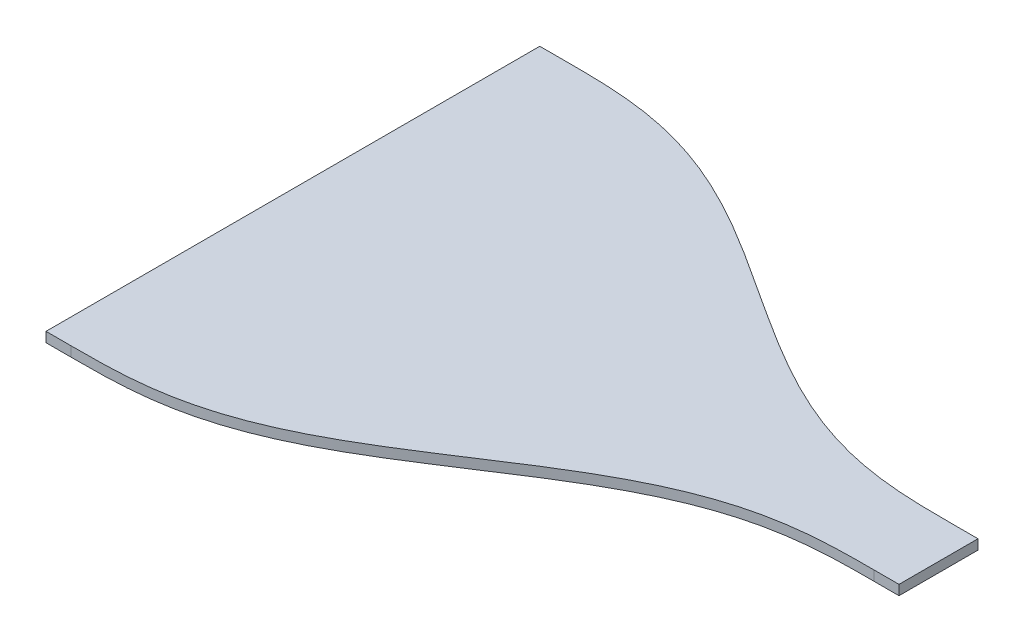
SolidWorks part; units mm, degrees
ref_plane "Front Plane" through (0, 0, 0) normal (0, 0, 1) x (1, 0, 0)
ref_plane "Top Plane" through (0, 0, 0) normal (0, 1, 0) x (1, 0, 0)
ref_plane "Right Plane" through (0, 0, 0) normal (1, 0, 0) x (0, 0, -1)
sketch "Sketch2" plane through (0, 0, 0) normal (0, 1, 0) x (1, 0, 0)
  line L3 (602.96, -40) -> (628.36, -40)
  line L5 (602.96, 40) -> (628.36, 40)
  line L6 (628.36, -40) -> (628.36, 40)
  line L7 (0, -250) -> (-25.4, -250)
  line L9 (0, 250) -> (-25.4, 250)
  line L10 (-25.4, -250) -> (-25.4, 250)
  spline S0 degree 4 poles (-60.296, 252.4276) (-59.6479, 252.3457) (-58.3512, 252.1869) (-55.7553, 251.8889) (-52.5053, 251.5632) (-49.2514, 251.2806) (-45.9942, 251.0374) (-43.3873, 250.865) (-40.1984, 250.6795) (-36.43, 250.4965) (-32.0757, 250.3311) (-27.1465, 250.1957) (-22.8206, 250.1151) (-19.1349, 250.0676) (-16.015, 250.0399) (-13.6544, 250.0237) (-10.2667, 250.0099) (-7.2918, 250.0014) (-1.3526, 249.9994) (1.6906, 250.0007) (8.7963, 249.9978) (12.3138, 249.984) (16.9488, 249.9592) (20.6777, 249.9212) (24.8671, 249.8682) (29.4538, 249.7806) (34.8728, 249.6388) (40.3351, 249.4443) (45.9673, 249.187) (53.1775, 248.7716) (61.9888, 248.109) (72.2406, 247.0857) (83.9178, 245.5398) (95.5332, 243.5951) (107.0739, 241.2402) (118.5221, 238.4733) (132.7008, 234.509) (146.6848, 229.8935) (160.4546, 224.6773) (174.0447, 218.911) (184.8318, 213.9822) (195.4918, 208.7847) (206.0311, 203.3471) (216.4219, 197.7179) (226.675, 191.9256) (239.3776, 184.488) (254.461, 175.2946) (271.8765, 164.277) (291.629, 151.4513) (311.331, 138.5487) (331.0835, 125.723) (350.987, 113.1315) (371.1397, 100.9404) (389.1095, 90.7617) (404.8218, 82.5056) (418.1282, 76.0178) (428.9153, 71.089) (439.795, 66.4727) (450.7673, 62.1931) (461.8688, 58.2603) (473.095, 54.6982) (484.4377, 51.5266) (495.8864, 48.7599) (505.9837, 46.6993) (514.687, 45.1895) (521.9646, 44.0987) (527.8037, 43.3243) (533.6484, 42.6455) (539.514, 42.0586) (545.3692, 41.5597) (551.2611, 41.1438) (558.313, 40.7359) (565.3355, 40.443) (572.0567, 40.2444) (578.9325, 40.1193) (583.9855, 40.0545) (589.9195, 40.018) (594.2835, 40.0022) (601.2169, 39.9993) (604.3716, 40.0006) (610.8787, 39.9983) (615.0042, 39.9853) (620.4039, 39.9539) (625.0734, 39.8964) (630.1528, 39.8043) (635.0101, 39.6689) (640.0581, 39.4787) (645.1061, 39.2211) (650.2649, 38.8825) (655.4615, 38.4475) (659.3679, 38.0439) (661.9588, 37.7362) (663.2561, 37.5724) knots 0 0 0 0 0 0.003383 0.006765 0.01353 0.016913 0.020295 0.023678 0.02706 0.03345 0.039839 0.046228 0.052617 0.055812 0.059006 0.062201 0.065396 0.071785 0.078174 0.085116 0.092059 0.099001 0.102472 0.105943 0.112885 0.119827 0.126769 0.133711 0.141334 0.148956 0.1642 0.179444 0.194688 0.209932 0.225176 0.24042 0.255664 0.286153 0.301397 0.316641 0.3321 0.347559 0.362803 0.378047 0.393291 0.408535 0.439023 0.469512 0.5 0.530488 0.560977 0.591465 0.621953 0.652441 0.6679 0.683359 0.698603 0.713847 0.729091 0.744336 0.75958 0.774824 0.790068 0.805312 0.812934 0.820556 0.828178 0.8358 0.843422 0.851044 0.858666 0.866289 0.880173 0.887115 0.894057 0.900999 0.907941 0.914884 0.921826 0.928215 0.934604 0.940994 0.947383 0.953772 0.960161 0.96655 0.97294 0.979705 0.98647 0.993235 1 1 1 1 1 construction
  spline S1 degree 4 poles (0, 250) (1.131, 250) (3.3588, 250) (8.7963, 249.9978) (12.3138, 249.984) (16.9488, 249.9592) (20.6777, 249.9212) (24.8671, 249.8682) (29.4538, 249.7806) (34.8728, 249.6388) (40.3351, 249.4443) (45.9673, 249.187) (53.1775, 248.7716) (61.9888, 248.109) (72.2406, 247.0857) (83.9178, 245.5398) (95.5332, 243.5951) (107.0739, 241.2402) (118.5221, 238.4733) (132.7008, 234.509) (146.6848, 229.8935) (160.4546, 224.6773) (174.0447, 218.911) (184.8318, 213.9822) (195.4918, 208.7847) (206.0311, 203.3471) (216.4219, 197.7179) (226.675, 191.9256) (239.3776, 184.488) (254.461, 175.2946) (271.8765, 164.277) (291.629, 151.4513) (311.331, 138.5487) (331.0835, 125.723) (350.987, 113.1315) (371.1397, 100.9404) (389.1095, 90.7617) (404.8218, 82.5056) (418.1282, 76.0178) (428.9153, 71.089) (439.795, 66.4727) (450.7673, 62.1931) (461.8688, 58.2603) (473.095, 54.6982) (484.4377, 51.5266) (495.8864, 48.7599) (505.9837, 46.6993) (514.687, 45.1895) (521.9646, 44.0987) (527.8037, 43.3243) (533.6484, 42.6455) (539.514, 42.0586) (545.3692, 41.5597) (551.2611, 41.1438) (558.313, 40.7359) (565.3355, 40.443) (572.0567, 40.2444) (578.9325, 40.1193) (583.9855, 40.0545) (589.9195, 40.018) (594.2835, 40.0022) (599.5892, 40) (601.829, 40) (602.96, 40) knots 0.078174 0.078174 0.078174 0.078174 0.078174 0.085116 0.092059 0.099001 0.102472 0.105943 0.112885 0.119827 0.126769 0.133711 0.141334 0.148956 0.1642 0.179444 0.194688 0.209932 0.225176 0.24042 0.255664 0.286153 0.301397 0.316641 0.3321 0.347559 0.362803 0.378047 0.393291 0.408535 0.439023 0.469512 0.5 0.530488 0.560977 0.591465 0.621953 0.652441 0.6679 0.683359 0.698603 0.713847 0.729091 0.744336 0.75958 0.774824 0.790068 0.805312 0.812934 0.820556 0.828178 0.8358 0.843422 0.851044 0.858666 0.866289 0.880173 0.887115 0.894057 0.900999 0.907941 0.914884 0.921826 0.921826 0.921826 0.921826 0.921826
  spline S2 degree 4 poles (-60.296, -252.4276) (-59.6479, -252.3457) (-58.3512, -252.1869) (-55.7553, -251.8889) (-52.5053, -251.5632) (-49.2514, -251.2806) (-45.9942, -251.0374) (-43.3873, -250.865) (-40.1984, -250.6795) (-36.43, -250.4965) (-32.0757, -250.3311) (-27.1465, -250.1957) (-22.8206, -250.1151) (-19.1349, -250.0676) (-16.015, -250.0399) (-13.6544, -250.0237) (-10.2667, -250.0099) (-7.2918, -250.0014) (-1.3526, -249.9994) (1.6906, -250.0007) (8.7963, -249.9978) (12.3138, -249.984) (16.9488, -249.9592) (20.6777, -249.9212) (24.8671, -249.8682) (29.4538, -249.7806) (34.8728, -249.6388) (40.3351, -249.4443) (45.9673, -249.187) (53.1775, -248.7716) (61.9888, -248.109) (72.2406, -247.0857) (83.9178, -245.5398) (95.5332, -243.5951) (107.0739, -241.2402) (118.5221, -238.4733) (132.7008, -234.509) (146.6848, -229.8935) (160.4546, -224.6773) (174.0447, -218.911) (184.8318, -213.9822) (195.4918, -208.7847) (206.0311, -203.3471) (216.4219, -197.7179) (226.675, -191.9256) (239.3776, -184.488) (254.461, -175.2946) (271.8765, -164.277) (291.629, -151.4513) (311.331, -138.5487) (331.0835, -125.723) (350.987, -113.1315) (371.1397, -100.9404) (389.1095, -90.7617) (404.8218, -82.5056) (418.1282, -76.0178) (428.9153, -71.089) (439.795, -66.4727) (450.7673, -62.1931) (461.8688, -58.2603) (473.095, -54.6982) (484.4377, -51.5266) (495.8864, -48.7599) (505.9837, -46.6993) (514.687, -45.1895) (521.9646, -44.0987) (527.8037, -43.3243) (533.6484, -42.6455) (539.514, -42.0586) (545.3692, -41.5597) (551.2611, -41.1438) (558.313, -40.7359) (565.3355, -40.443) (572.0567, -40.2444) (578.9325, -40.1193) (583.9855, -40.0545) (589.9195, -40.018) (594.2835, -40.0022) (601.2169, -39.9993) (604.3716, -40.0006) (610.8787, -39.9983) (615.0042, -39.9853) (620.4039, -39.9539) (625.0734, -39.8964) (630.1528, -39.8043) (635.0101, -39.6689) (640.0581, -39.4787) (645.1061, -39.2211) (650.2649, -38.8825) (655.4615, -38.4475) (659.3679, -38.0439) (661.9588, -37.7362) (663.2561, -37.5724) knots 0 0 0 0 0 0.003383 0.006765 0.01353 0.016913 0.020295 0.023678 0.02706 0.03345 0.039839 0.046228 0.052617 0.055812 0.059006 0.062201 0.065396 0.071785 0.078174 0.085116 0.092059 0.099001 0.102472 0.105943 0.112885 0.119827 0.126769 0.133711 0.141334 0.148956 0.1642 0.179444 0.194688 0.209932 0.225176 0.24042 0.255664 0.286153 0.301397 0.316641 0.3321 0.347559 0.362803 0.378047 0.393291 0.408535 0.439023 0.469512 0.5 0.530488 0.560977 0.591465 0.621953 0.652441 0.6679 0.683359 0.698603 0.713847 0.729091 0.744336 0.75958 0.774824 0.790068 0.805312 0.812934 0.820556 0.828178 0.8358 0.843422 0.851044 0.858666 0.866289 0.880173 0.887115 0.894057 0.900999 0.907941 0.914884 0.921826 0.928215 0.934604 0.940994 0.947383 0.953772 0.960161 0.96655 0.97294 0.979705 0.98647 0.993235 1 1 1 1 1 construction
  spline S3 degree 4 poles (0, -250) (1.131, -250) (3.3588, -250) (8.7963, -249.9978) (12.3138, -249.984) (16.9488, -249.9592) (20.6777, -249.9212) (24.8671, -249.8682) (29.4538, -249.7806) (34.8728, -249.6388) (40.3351, -249.4443) (45.9673, -249.187) (53.1775, -248.7716) (61.9888, -248.109) (72.2406, -247.0857) (83.9178, -245.5398) (95.5332, -243.5951) (107.0739, -241.2402) (118.5221, -238.4733) (132.7008, -234.509) (146.6848, -229.8935) (160.4546, -224.6773) (174.0447, -218.911) (184.8318, -213.9822) (195.4918, -208.7847) (206.0311, -203.3471) (216.4219, -197.7179) (226.675, -191.9256) (239.3776, -184.488) (254.461, -175.2946) (271.8765, -164.277) (291.629, -151.4513) (311.331, -138.5487) (331.0835, -125.723) (350.987, -113.1315) (371.1397, -100.9404) (389.1095, -90.7617) (404.8218, -82.5056) (418.1282, -76.0178) (428.9153, -71.089) (439.795, -66.4727) (450.7673, -62.1931) (461.8688, -58.2603) (473.095, -54.6982) (484.4377, -51.5266) (495.8864, -48.7599) (505.9837, -46.6993) (514.687, -45.1895) (521.9646, -44.0987) (527.8037, -43.3243) (533.6484, -42.6455) (539.514, -42.0586) (545.3692, -41.5597) (551.2611, -41.1438) (558.313, -40.7359) (565.3355, -40.443) (572.0567, -40.2444) (578.9325, -40.1193) (583.9855, -40.0545) (589.9195, -40.018) (594.2835, -40.0022) (599.5892, -40) (601.829, -40) (602.96, -40) knots 0.078174 0.078174 0.078174 0.078174 0.078174 0.085116 0.092059 0.099001 0.102472 0.105943 0.112885 0.119827 0.126769 0.133711 0.141334 0.148956 0.1642 0.179444 0.194688 0.209932 0.225176 0.24042 0.255664 0.286153 0.301397 0.316641 0.3321 0.347559 0.362803 0.378047 0.393291 0.408535 0.439023 0.469512 0.5 0.530488 0.560977 0.591465 0.621953 0.652441 0.6679 0.683359 0.698603 0.713847 0.729091 0.744336 0.75958 0.774824 0.790068 0.805312 0.812934 0.820556 0.828178 0.8358 0.843422 0.851044 0.858666 0.866289 0.880173 0.887115 0.894057 0.900999 0.907941 0.914884 0.921826 0.921826 0.921826 0.921826 0.921826
  dimension "D1" = 25.4
  dimension "D2" = 25.4
extrude "Boss-Extrude1" add sketch "Sketch2" along normal blind 10
